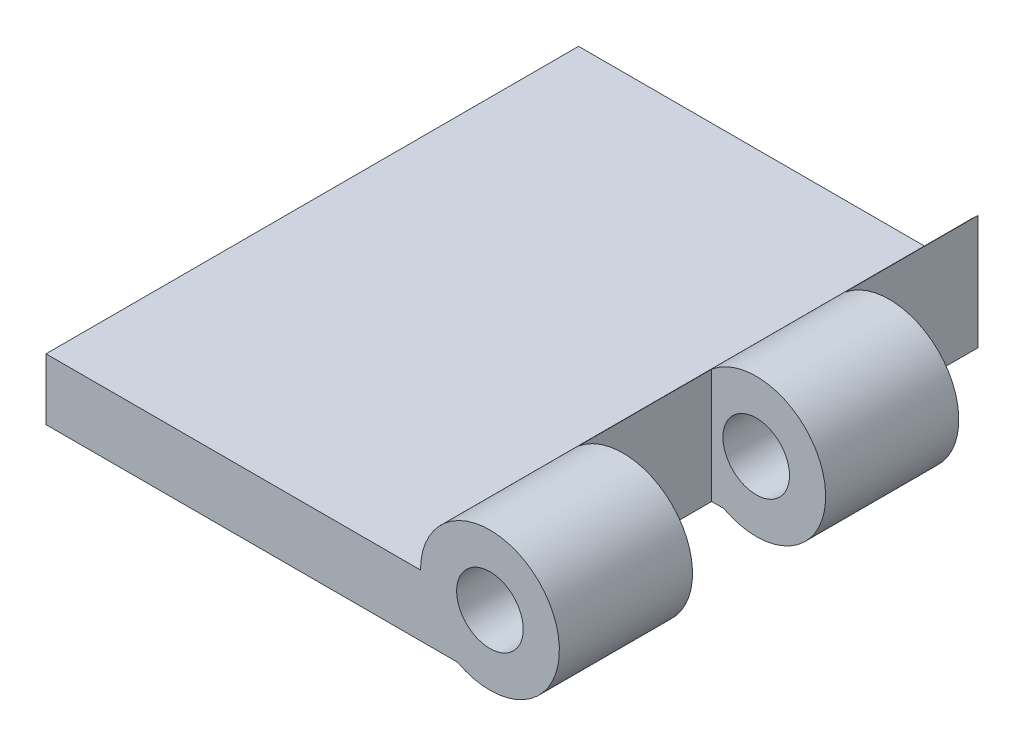
SolidWorks part; units mm, degrees
ref_plane "Front Plane" through (0, 0, 0) normal (0, 0, 1) x (1, 0, 0)
ref_plane "Top Plane" through (0, 0, 0) normal (0, 1, 0) x (1, 0, 0)
ref_plane "Right Plane" through (0, 0, 0) normal (1, 0, 0) x (0, 0, -1)
sketch "Sketch1" plane through (0, 0, 0) normal (0, 0, 1) x (1, 0, 0)
  line L1 (1.1435, 262.7258) -> (-38.1, 262.7258)
  line L3 (-2.3772, 268.5772) -> (-38.1, 268.5772)
  line L4 (-38.1, 262.7258) -> (-38.1, 268.5772)
  circle A0 centre (4.2456, 268.5772) radius 3.175
  arc A1 (1.1435, 262.7258) -> (-2.3772, 268.5772) centre (4.2456, 268.5772) ccw
extrude "Boss-Extrude1" add sketch "Sketch1" against normal blind 50.8
sketch "Sketch2" plane through (0, 268.5772, 0) normal (0, 1, 0) x (1, 0, 0)
  line L1 (10.8684, 12.7) -> (0, 12.7)
  line L2 (0, 12.7) -> (0, 25.4)
  line L3 (0, 25.4) -> (10.8684, 25.4)
  line L4 (10.8684, 12.7) -> (10.8684, 25.4)
  line L5 (10.8684, 0) -> (10.8684, 50.8) construction
  line L6 (-2.3772, 0) -> (10.8684, 0) construction
  line L8 (10.8684, 50.8) -> (0, 50.8)
  line L9 (10.8684, 50.8) -> (10.8684, 38.1)
  line L10 (10.8684, 38.1) -> (0, 38.1)
  line L11 (0, 50.8) -> (0, 38.1)
  dimension "D1" = 12.7
  dimension "D2" = 12.7
extrude "Cut-Extrude1" cut sketch "Sketch2" against normal through all and the other way through all
